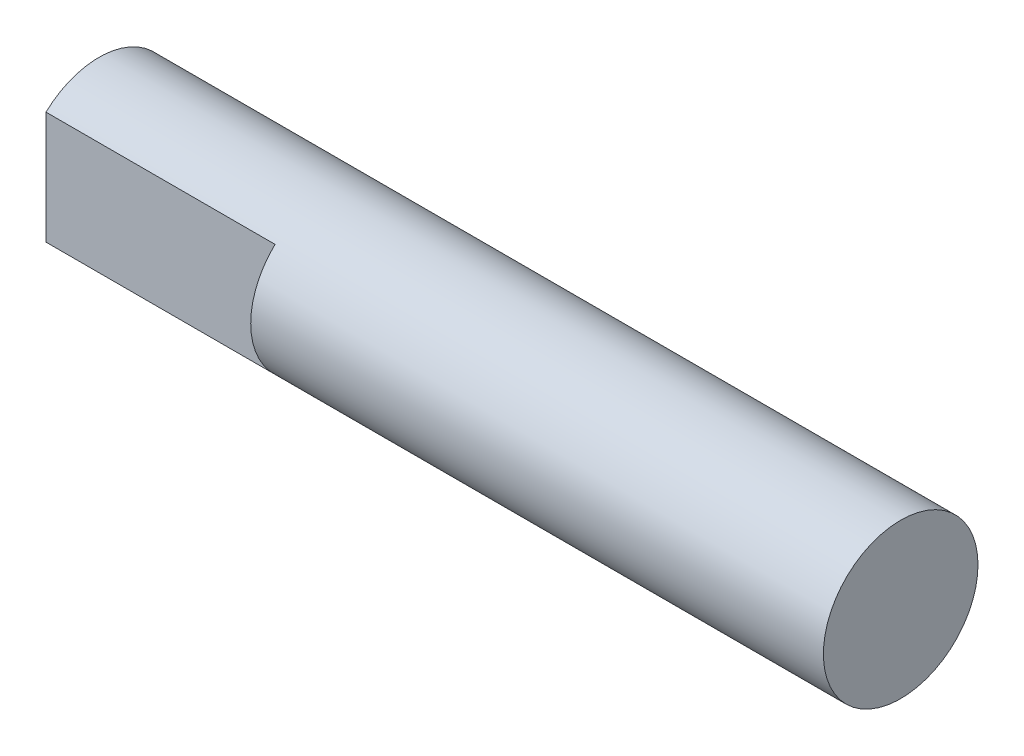
SolidWorks part; units mm, degrees
ref_plane "Front Plane" through (0, 0, 0) normal (0, 0, 1) x (1, 0, 0)
ref_plane "Top Plane" through (0, 0, 0) normal (0, 1, 0) x (1, 0, 0)
ref_plane "Right Plane" through (0, 0, 0) normal (1, 0, 0) x (0, 0, -1)
sketch "Sketch1" plane through (0, 0, 0) normal (1, 0, 0) x (0, 0, -1)
  circle A0 centre (0, 0) radius 2.7
  dimension "D1" = 5.4
extrude "Boss-Extrude1" add sketch "Sketch1" along normal mid plane 37
sketch "Sketch2" plane through (18.5, 0, 0) normal (1, 0, 0) x (0, 0, -1)
  line L0 (-1.85, 1.9666) -> (-1.85, -1.9666)
  line L1 (1.85, 1.9666) -> (1.85, -1.9666)
  arc A0 (-1.85, 1.9666) -> (-1.85, -1.9666) centre (0, 0) ccw
  arc A1 (1.85, -1.9666) -> (1.85, 1.9666) centre (0, 0) ccw
  dimension "D3" = 5.4
  dimension "D1" = 3.7
  dimension "D2" = 1.85
extrude "Cut-Extrude1" cut sketch "Sketch2" against normal blind 8
sketch "Sketch3" plane through (18.5, 0, 0) normal (1, 0, 0) x (0, 0, -1)
  circle A0 centre (0, 0) radius 1
  dimension "D1" = 2
extrude "Cut-Extrude2" cut sketch "Sketch3" against normal blind 6
mirror "Mirror1" about plane through (0, 0, 0) normal (1, 0, 0) of "Cut-Extrude1", "Cut-Extrude2"
sketch "Croquis1" plane through (0, 0, -1.85) normal (0, 0, -1) x (-1, 0, 0)
  line L0 (-9.5, -2.7) -> (-9.5, 3.1185)
  line L1 (-18.5, -2.7) -> (18.5, -2.7) construction
  line L2 (-9.5, -24.745) -> (-9.5, 7.1869) construction
  line L3 (-9.5, 3.1185) -> (-19.1199, 3.1185)
  line L4 (-19.1199, 3.1185) -> (-19.1199, -3.6245)
  line L5 (-19.1199, -3.6245) -> (-9.5, -3.6245)
  line L6 (-9.5, -3.6245) -> (-9.5, -2.7)
extrude "Cortar-Extruir1" cut sketch "Croquis1" against normal up to next and the other way up to next
